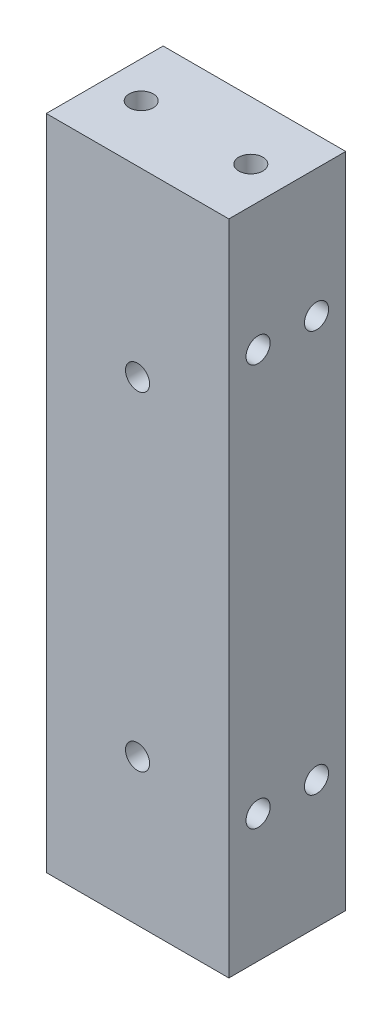
SolidWorks part; units mm, degrees
ref_plane "Front Plane" through (0, 0, 0) normal (0, 0, 1) x (1, 0, 0)
ref_plane "Top Plane" through (0, 0, 0) normal (0, 1, 0) x (1, 0, 0)
ref_plane "Right Plane" through (0, 0, 0) normal (1, 0, 0) x (0, 0, -1)
sketch "Sketch1" plane through (0, 0, 0) normal (0, 1, 0) x (1, 0, 0)
  line L1 (-12.5, -8) -> (12.5, -8)
  line L2 (-12.5, -8) -> (-12.5, 8)
  line L3 (-12.5, 8) -> (12.5, 8)
  line L4 (12.5, -8) -> (12.5, 8)
  line L5 (-12.5, -8) -> (12.5, 8) construction
  line L6 (-12.5, 8) -> (12.5, -8) construction
  point P0 (0, 0)
  dimension "D1" = 25
  dimension "D2" = 16
extrude "Boss-Extrude1" add sketch "Sketch1" along normal blind 90
hole_wizard "M4x0.7 Tapped Hole1" positions "Sketch2" profile "Sketch4" tap size "M4x0.7" standard "ANSI Metric"
sketch "Sketch2" plane through (0, 90, 0) normal (0, 1, 0) x (1, 0, 0)
  line L0 (-7.5, 0) -> (7.5, 0)
  point P1 (-7.5, 0)
  point P2 (7.5, 0)
  point P6 (0, 0)
  dimension "D1" = 15
sketch "Sketch4" plane through (-7.5, 90, 0) normal (1, 0, 0) x (0, 0, 1)
  line L0 (0, 0) -> (0, 8.9914)
  line L1 (0, 8.9914) -> (1.65, 8)
  line L2 (1.65, 8) -> (1.65, 0)
  line L5 (1.65, 0) -> (0, 0)
  line L10 (0, 8.9914) -> (-1.65, 8) construction
  line L11 (0, -6.35) -> (0, 107.95) construction
  dimension "Tap Drill Dia." = 3.3
  dimension "Tap Drill Depth" = 8
  dimension "Drill Angle" = 118
cosmetic thread "Hole Thread1" parameters "D1"=8, "D2"=4
cosmetic thread "Hole Thread2" parameters "D1"=8, "D2"=4
hole_wizard "M4x0.7 Tapped Hole2" positions "Sketch5" profile "Sketch6" tap size "M4x0.7" standard "ANSI Metric"
sketch "Sketch5" plane through (0, 0, 0) normal (0, -1, 0) x (-1, 0, 0)
  line L0 (-7.5, 0) -> (7.5, 0)
  point P1 (-7.5, 0)
  point P2 (7.5, 0)
  point P5 (0, 0)
  dimension "D1" = 15
sketch "Sketch6" plane through (7.5, 0, 0) normal (1, 0, 0) x (0, 0, -1)
  line L0 (0, 0) -> (0, 12.9914)
  line L1 (0, 12.9914) -> (1.65, 12)
  line L2 (1.65, 12) -> (1.65, 0)
  line L5 (1.65, 0) -> (0, 0)
  line L10 (0, 12.9914) -> (-1.65, 12) construction
  line L11 (0, -6.35) -> (0, 107.95) construction
  dimension "Tap Drill Dia." = 3.3
  dimension "Tap Drill Depth" = 12
  dimension "Drill Angle" = 118
cosmetic thread "Hole Thread3" parameters "D1"=8, "D2"=4
cosmetic thread "Hole Thread4" parameters "D1"=8, "D2"=4
hole_wizard "M4x0.7 Tapped Hole3" positions "Sketch10" profile "Sketch11" tap size "M4x0.7" standard "ANSI Metric" end condition through all
sketch "Sketch10" plane through (0, 0, -8) normal (0, 0, -1) x (-1, 0, 0)
  line L0 (-12.5, 90) -> (-12.5, 0) construction
  line L1 (-12.5, 0) -> (12.5, 0) construction
  point P0 (0, 20)
  point P14 (0, 65)
  point P15 (7.6211, 20)
  point P16 (15, 65)
  point P17 (15, 20)
  point P18 (0, 0)
  point P19 (0, 0)
  dimension "D1" = 12.5
  dimension "D2" = 20
  dimension "D5" = 45
  dimension "D3" = 2
  dimension "D4" = 2
sketch "Sketch11" plane through (0, 20, -8) normal (1, 0, 0) x (0, 1, 0)
  line L0 (0, 0) -> (0, 16)
  line L1 (0, 16) -> (1.65, 16)
  line L2 (1.65, 16) -> (1.65, 0)
  line L5 (1.65, 0) -> (0, 0)
  line L11 (0, -6.35) -> (0, 107.95) construction
  dimension "Thru Tap Drill Dia." = 3.3
  dimension "Thru Tap Drill Depth" = 16
cosmetic thread "Hole Thread5" parameters "D2"=4
cosmetic thread "Hole Thread8" parameters "D2"=4
hole_wizard "M4x0.7 Tapped Hole4" positions "Sketch12" profile "Sketch13" tap size "M4x0.7" standard "ANSI Metric"
sketch "Sketch12" plane through (-12.5, 0, 0) normal (-1, 0, 0) x (0, 0, 1)
  line L4 (-4, 17.5) -> (4, 17.5)
  line L5 (-4, 17.5) -> (-4, 72.5)
  line L6 (-4, 72.5) -> (4, 72.5)
  line L7 (4, 17.5) -> (4, 72.5)
  line L8 (-4, 17.5) -> (4, 72.5) construction
  line L9 (-4, 72.5) -> (4, 17.5) construction
  line L10 (-8, 90) -> (-8, 0) construction
  point P130 (0, 45)
  point P134 (-8, 45)
  point P137 (-4, 72.5)
  point P140 (4, 72.5)
  point P143 (-4, 17.5)
  point P146 (4, 17.5)
  dimension "D1" = 55
  dimension "D2" = 8
sketch "Sketch13" plane through (-12.5, 17.5, 4) normal (0, 1, 0) x (0, 0, 1)
  line L0 (0, 0) -> (0, 8.9914)
  line L1 (0, 8.9914) -> (1.65, 8)
  line L2 (1.65, 8) -> (1.65, 0)
  line L5 (1.65, 0) -> (0, 0)
  line L10 (0, 8.9914) -> (-1.65, 8) construction
  line L11 (0, -6.35) -> (0, 107.95) construction
  dimension "Tap Drill Dia." = 3.3
  dimension "Tap Drill Depth" = 8
  dimension "Drill Angle" = 118
cosmetic thread "Hole Thread9" parameters "D1"=8, "D2"=4
cosmetic thread "Hole Thread10" parameters "D1"=8, "D2"=4
cosmetic thread "Hole Thread11" parameters "D1"=8, "D2"=4
cosmetic thread "Hole Thread12" parameters "D1"=8, "D2"=4
mirror "Mirror1" about plane through (0, 0, 0) normal (1, 0, 0) of "M4x0.7 Tapped Hole4"
cosmetic thread "Hole Thread13" parameters "D1"=8, "D2"=4
cosmetic thread "Hole Thread14" parameters "D1"=8, "D2"=4
cosmetic thread "Hole Thread15" parameters "D1"=8, "D2"=4
cosmetic thread "Hole Thread16" parameters "D1"=8, "D2"=4
